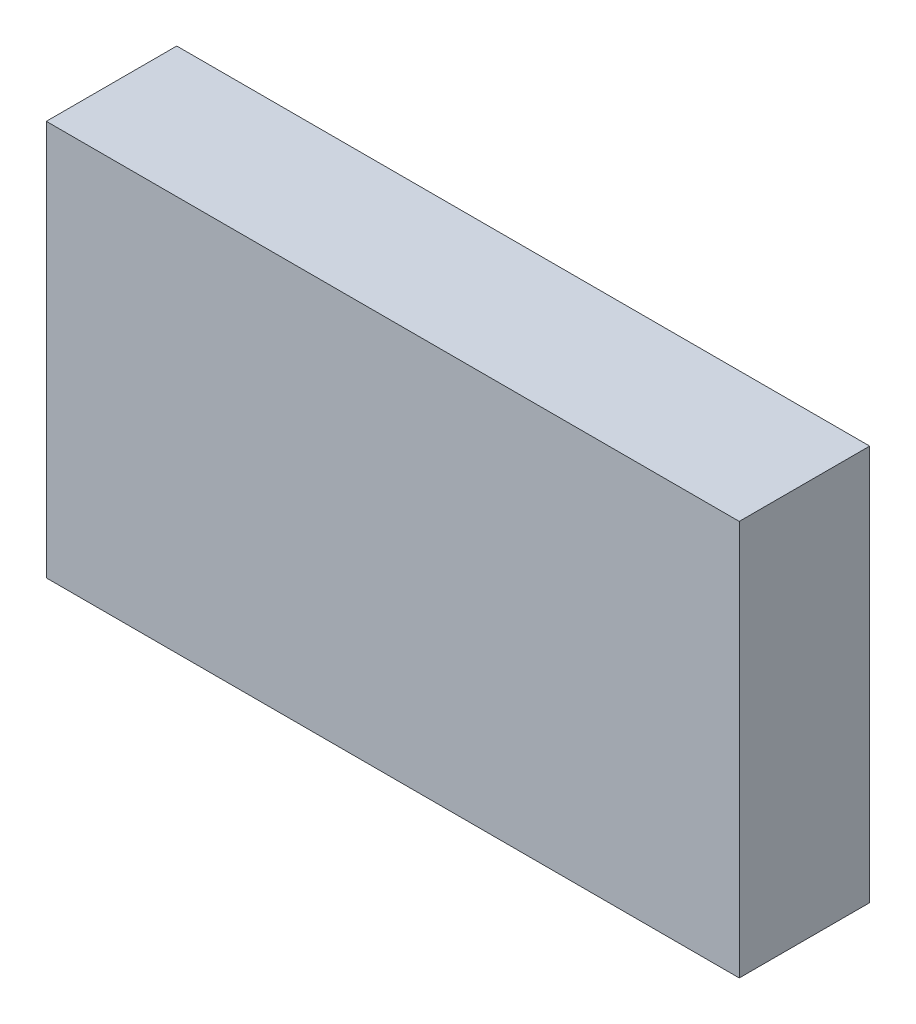
SolidWorks part; units mm, degrees
ref_plane "Front Plane" through (0, 0, 0) normal (0, 0, 1) x (1, 0, 0)
ref_plane "Top Plane" through (0, 0, 0) normal (0, 1, 0) x (1, 0, 0)
ref_plane "Right Plane" through (0, 0, 0) normal (1, 0, 0) x (0, 0, -1)
sketch "Sketch1" plane through (0, 0, 0) normal (0, 0, 1) x (1, 0, 0)
  line L1 (-54.5683, 42.0089) -> (51.6811, 42.0089)
  line L2 (-54.5683, 42.0089) -> (-54.5683, -18.6225)
  line L3 (-54.5683, -18.6225) -> (51.6811, -18.6225)
  line L4 (51.6811, 42.0089) -> (51.6811, -18.6225)
extrude "Boss-Extrude1" add sketch "Sketch1" along normal blind 20
